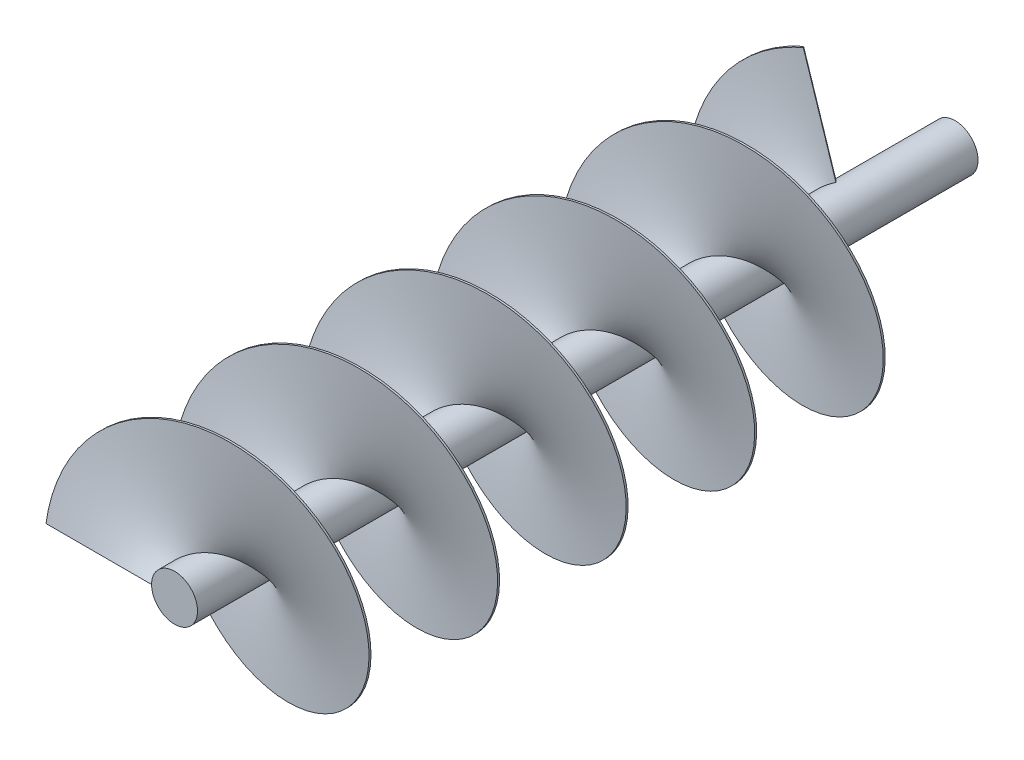
SolidWorks part; units mm, degrees
ref_plane "Alzado" through (0, 0, 0) normal (0, 0, 1) x (1, 0, 0)
ref_plane "Planta" through (0, 0, 0) normal (0, 1, 0) x (1, 0, 0)
ref_plane "Vista lateral" through (0, 0, 0) normal (1, 0, 0) x (0, 0, -1)
sketch "Croquis1" plane through (0, 0, 0) normal (0, 0, 1) x (1, 0, 0)
  circle A0 centre (0, 0) radius 5
  dimension "D1" = 10
extrude "Saliente-Extruir1" add sketch "Croquis1" along normal blind 160
sketch "Croquis2" plane through (0, 0, 160) normal (0, 0, 1) x (1, 0, 0)
  circle A0 centre (0, 0) radius 5
curve "Hélice/Espiral2" pitch 28 height 145.6 turns 5.2
ref_plane "Plano1" through (-5, 0, 160) normal (0, 0.7465, -0.6654) x (1, 0, 0)
sketch "Croquis3" plane through (-5, 0, 160) normal (0, 0.7465, -0.6654) x (1, 0, 0)
  line L0 (0, 0) -> (0, 0.5)
  line L1 (0, 0.5) -> (-23, 0.5)
  line L2 (-23, 0.5) -> (-23, 0)
  line L3 (-23, 0) -> (0, 0)
  dimension "D1" = 23
  dimension "D2" = 0.5
sweep "Barrer1" add profiles "Croquis3" path "Hélice/Espiral2"
sketch "Croquis4" plane through (0, 0, 0) normal (0, 0, -1) x (-1, 0, 0)
  circle A0 centre (0, 0) radius 3.05
  dimension "D1" = 6.1
extrude "Cortar-Extruir1" cut sketch "Croquis4" against normal blind 10
sketch "Croquis6" plane through (0, 0, 0) normal (0, 0, -1) x (-1, 0, 0)
  circle A0 centre (0, 0) radius 5
  circle A1 centre (0, 0) radius 3.05
  dimension "D1" = 10
extrude "Saliente-Extruir2" add sketch "Croquis6" along normal blind 10
